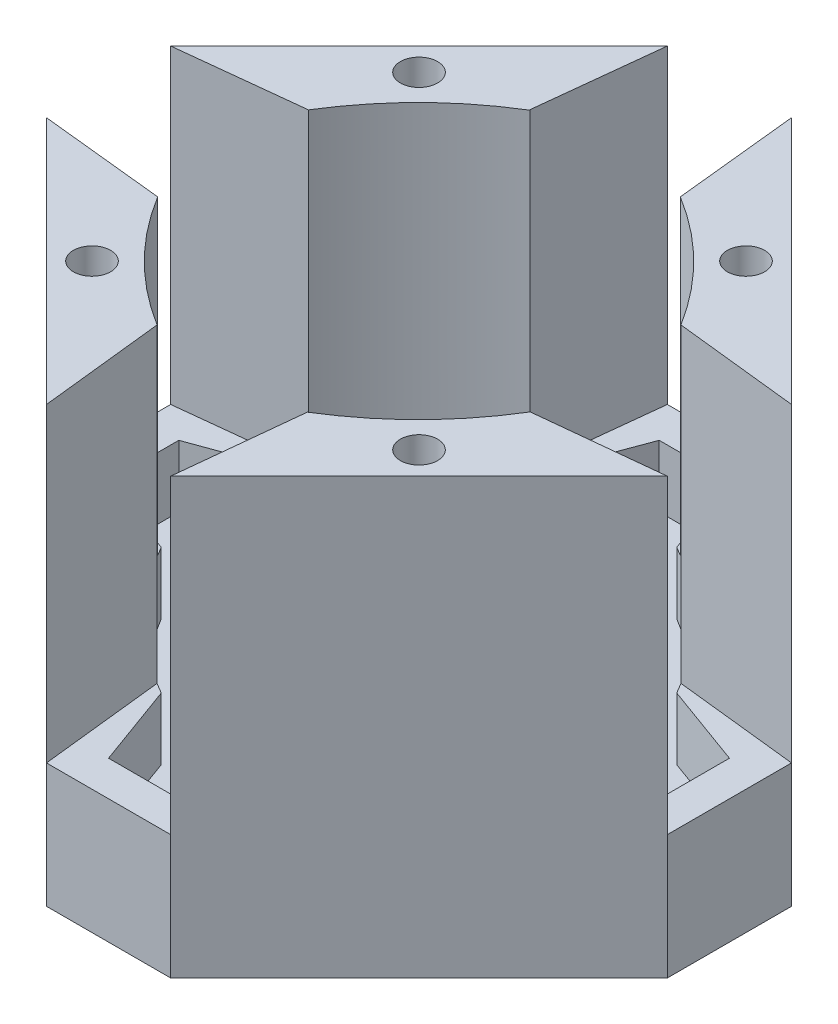
SolidWorks part; units mm, degrees
ref_plane "Front Plane" through (0, 0, 0) normal (0, 0, 1) x (1, 0, 0)
ref_plane "Top Plane" through (0, 0, 0) normal (0, 1, 0) x (1, 0, 0)
ref_plane "Right Plane" through (0, 0, 0) normal (1, 0, 0) x (0, 0, -1)
sketch "Sketch1" plane through (0, 0, 0) normal (0, 1, 0) x (1, 0, 0)
  line L1 (-25, -25) -> (25, -25)
  line L2 (-25, -25) -> (-25, 25)
  line L3 (-25, 25) -> (25, 25)
  line L4 (25, -25) -> (25, 25)
  line L5 (-25, -25) -> (25, 25) construction
  line L6 (-25, 25) -> (25, -25) construction
  circle A0 centre (0, 0) radius 4.5
  point P0 (0, 0)
  dimension "D3" = 9
  dimension "D1" = 50
  dimension "D2" = 50
extrude "Boss-Extrude1" add sketch "Sketch1" along normal blind 5
sketch "Sketch2" plane through (0, 5, 0) normal (0, 1, 0) x (1, 0, 0)
  line L0 (-25, 25) -> (25, -25) construction
  line L1 (25, 25) -> (-25, -25) construction
  line L2 (0, 0) -> (-0.0589, 16.2499) construction
  line L3 (-25, 25) -> (-25, -25) construction
  line L4 (0, -25) -> (0, 25) construction
  line L5 (-25, 25) -> (-25, 5)
  line L6 (-25, 25) -> (-5, 25)
  line L7 (25, 25) -> (-25, 25) construction
  line L8 (-25, 5) -> (-5, 25)
  line L9 (-25, -25) -> (25, -25) construction
  line L10 (25, -25) -> (5, -25)
  line L11 (25, -25) -> (25, -5)
  line L12 (5, -25) -> (25, -5)
  line L13 (-25, -25) -> (-25, -5)
  line L14 (-5, -25) -> (-25, -5)
  line L15 (-25, -25) -> (-5, -25)
  line L16 (25, 25) -> (25, 5)
  line L17 (25, 25) -> (5, 25)
  line L18 (25, 5) -> (5, 25)
  circle A1 centre (-0.0589, 16.2499) radius 2
  circle A2 centre (16.2499, -0.0589) radius 2
  circle A3 centre (0.0589, -16.2499) radius 2
  circle A4 centre (-16.2499, 0.0589) radius 2
  dimension "D1" = 20
  dimension "D3" = 20
  dimension "D2" = 16.25
extrude "Cut-Extrude1" cut sketch "Sketch2" against normal through all
sketch "Sketch3" plane through (0, 5, 0) normal (0, 1, 0) x (1, 0, 0)
  line L0 (15, 15) -> (12.5, 12.5) construction
  line L1 (5, 25) -> (25, 5) construction
  line L2 (-5, -25) -> (-25, -5) construction
  line L3 (0, -4.5) -> (-0.4286, -4.9286)
  line L4 (-22.1716, 2.8284) -> (-2.8284, 22.1716) construction
  line L5 (-7.8284, 22.1716) -> (-25, 5)
  line L7 (2.8284, 22.1716) -> (22.1716, 2.8284) construction
  line L9 (22.1716, -2.8284) -> (2.8284, -22.1716) construction
  line L10 (-5, -25) -> (5, -25) construction
  line L11 (-2.8284, -22.1716) -> (-22.1716, -2.8284) construction
  line L12 (-22.1716, -2.8284) -> (-2.8284, -22.1716)
  line L13 (-25, 5) -> (-22.1716, 7.8284) construction
  line L14 (-25, 5) -> (-5, 25) construction
  line L15 (-25, -5) -> (-22.1716, -7.8284) construction
  line L16 (-22.1716, -2.8284) -> (-22.1716, 2.8284)
  line L17 (-22.1716, 7.8284) -> (-25, 5)
  line L18 (-25, 5) -> (-25, -5)
  line L19 (-25, -5) -> (-22.1716, -7.8284)
  line L20 (-5, -25) -> (0, -25)
  line L21 (-22.1716, -7.8284) -> (-5, -25)
  line L22 (-2.8284, -22.1716) -> (2.8284, -22.1716)
  line L23 (5, -25) -> (-5, -25)
  line L24 (7.8284, -22.1716) -> (5, -25)
  line L27 (22.1716, -7.8284) -> (25, -5)
  line L28 (25, -5) -> (25, 5)
  line L29 (22.1716, 2.8284) -> (22.1716, -2.8284)
  line L30 (2.8284, 22.1716) -> (22.1716, 2.8284)
  line L31 (7.8284, 22.1716) -> (25, 5)
  line L32 (-5, 25) -> (5, 25)
  line L33 (-7.8284, 22.1716) -> (-5, 25)
  line L34 (2.8284, 22.1716) -> (-2.8284, 22.1716)
  line L35 (-22.1716, 7.8284) -> (-7.8284, 22.1716)
  line L36 (-22.1716, 2.8284) -> (-2.8284, 22.1716)
  line L37 (2.8284, -22.1716) -> (22.1716, -2.8284)
  line L38 (7.8284, -22.1716) -> (22.1716, -7.8284)
  line L39 (-22.1716, 7.8284) -> (-7.8284, 22.1716)
  circle A1 centre (0, 0) radius 4.5 construction
  line M24 (25, -5) -> (25, 5)
  line M25 (25, 5) -> (5, 25)
  line M26 (5, 25) -> (-5, 25)
  line M27 (-5, 25) -> (-25, 5)
  line M28 (-25, 5) -> (-25, -5)
  line M29 (-25, -5) -> (-5, -25)
  line M30 (-5, -25) -> (5, -25)
  line M31 (5, -25) -> (25, -5)
  dimension "D1" = 4
  dimension "D2" = 4
extrude "Boss-Extrude2" add sketch "Sketch3" along normal blind 30 contours L5 L37 L22 L12 L16 L36 L34 L30 L29 M31 M24 M25 M26 M27 M28 M29 M30
sketch "Sketch4" plane through (0, 35, 0) normal (0, 1, 0) x (1, 0, 0)
  line L1 (-22.1716, -2.8284) -> (-2.8284, -22.1716) construction
  line L4 (-7.3747, -17.6253) -> (-17.537, -7.463)
  line L5 (-15.4156, -5.3417) -> (-22.1716, -2.8284)
  line L6 (-22.1716, -2.8284) -> (-17.537, -7.463)
  line L9 (-17.537, -7.463) -> (-2.8284, -22.1716)
  line L10 (-2.8284, -22.1716) -> (-5.2533, -15.504)
  line L11 (-7.3747, -17.6253) -> (-2.8284, -22.1716)
  line L15 (2.8284, 22.1716) -> (7.463, 17.537)
  line L16 (5.3417, 15.4156) -> (2.8284, 22.1716)
  line L17 (22.1716, 2.8284) -> (15.504, 5.2533)
  line L18 (7.463, 17.537) -> (22.1716, 2.8284)
  line L22 (-5.3417, 15.4156) -> (-2.8284, 22.1716)
  line L23 (-22.1716, 2.8284) -> (-15.504, 5.2533)
  line L24 (-7.463, 17.537) -> (-22.1716, 2.8284)
  line L25 (-2.8284, 22.1716) -> (-7.463, 17.537)
  line L26 (22.1716, -2.8284) -> (17.537, -7.463)
  line L27 (15.4156, -5.3417) -> (22.1716, -2.8284)
  line L28 (2.8284, -22.1716) -> (5.2533, -15.504)
  line L29 (17.537, -7.463) -> (2.8284, -22.1716)
  spline S0 degree 3 poles (-15.4156, -5.3417) (-12.8732, -9.7779) (-9.4021, -13.1087) (-5.2533, -15.504) knots 0 0 0 0 1 1 1 1
  spline S1 degree 3 poles (5.3417, 15.4156) (9.7779, 12.8732) (13.1087, 9.4021) (15.504, 5.2533) knots 0 0 0 0 1 1 1 1
  spline S2 degree 3 poles (-5.3417, 15.4156) (-9.7779, 12.8732) (-13.1087, 9.4021) (-15.504, 5.2533) knots 0 0 0 0 1 1 1 1
  spline S3 degree 3 poles (15.4156, -5.3417) (12.8732, -9.7779) (9.4021, -13.1087) (5.2533, -15.504) knots 0 0 0 0 1 1 1 1
  line M17 (22.1716, -2.8284) -> (2.8284, -22.1716)
  line M19 (-2.8284, -22.1716) -> (-22.1716, -2.8284)
  line M21 (-22.1716, 2.8284) -> (-2.8284, 22.1716)
  line M23 (2.8284, 22.1716) -> (22.1716, 2.8284)
  dimension "D1" = 3
  dimension "D3" = 3
extrude "Boss-Extrude3" add sketch "Sketch4" against normal blind 30 contours S2 L22 L23 M21 | L16 S1 L17 M23 | L27 S3 L28 M17 | S0 L5 L10 M19
sketch "Sketch7" plane through (0, 35, 0) normal (0, 1, 0) x (1, 0, 0)
  line L2 (-25, 5) -> (-25, -5)
  line L6 (0, 25) -> (0, -25) construction
  line L7 (5, 25) -> (-5, 25) construction
  line L8 (-5, -25) -> (5, -25) construction
  line L9 (-15, 15) -> (15, -15) construction
  line L10 (-5, 25) -> (-25, 5) construction
  line L11 (5, -25) -> (25, -5) construction
  line L12 (-25, 5) -> (-15, 6.094)
  line L13 (-25, -5) -> (-15, -6.0437)
  line L14 (-15, -6.0437) -> (-15, 6.094)
  line L15 (25, -5) -> (15, -6.0437)
  line L16 (25, 5) -> (25, -5)
  line L17 (25, 5) -> (15, 6.094)
  line L18 (15, -6.0437) -> (15, 6.094)
  line L19 (-5, -25) -> (5, -25)
  line L20 (-5, -25) -> (-6.094, -15)
  line L21 (6.0437, -15) -> (-6.094, -15)
  line L22 (5, -25) -> (6.0437, -15)
  line L23 (5, 25) -> (6.0437, 15)
  line L24 (-5, 25) -> (5, 25)
  line L25 (-5, 25) -> (-6.094, 15)
  line L26 (6.0437, 15) -> (-6.094, 15)
  spline S0 degree 3 poles (-5.3417, 15.4156) (-9.7779, 12.8732) (-13.1087, 9.4021) (-15.504, 5.2533) knots 0 0 0 0 1 1 1 1 construction
  spline S1 degree 3 poles (-15.4156, -5.3417) (-12.8732, -9.7779) (-9.4021, -13.1087) (-5.2533, -15.504) knots 0 0 0 0 1 1 1 1 construction
extrude "Cut-Extrude5" cut sketch "Sketch7" against normal blind 25
sketch "Sketch9" plane through (0, 5, 0) normal (0, 1, 0) x (1, 0, 0)
  line L0 (-25, 0) -> (25, 0) construction
  line L1 (-25, 5) -> (-25, -5) construction
  line L2 (25, -5) -> (25, 5) construction
  line L3 (-15, 15) -> (15, -15) construction
  line L4 (-5, 25) -> (-25, 5) construction
  line L5 (5, -25) -> (25, -5) construction
  circle A0 centre (0, 9.4999) radius 2.5
  circle A1 centre (-0.0589, 16.2499) radius 2 construction
  circle A2 centre (0, -9.4999) radius 2.5
  circle A3 centre (9.4999, 0) radius 2.5
  circle A4 centre (-9.4999, 0) radius 2.5
  dimension "D1" = 6.75
  dimension "D2" = 5
extrude "Cut-Extrude8" cut sketch "Sketch9" against normal through all
sketch "Sketch10" plane through (0, 35, 0) normal (0, 1, 0) x (1, 0, 0)
  line L0 (15, 15) -> (-15, -15) construction
  line L1 (25, 5) -> (5, 25) construction
  line L2 (-25, -5) -> (-5, -25) construction
  line L3 (25, 0) -> (-25, 0) construction
  line L4 (25, -5) -> (25, 5) construction
  line L5 (-25, 5) -> (-25, -5) construction
  line L6 (0, 25) -> (0, -25) construction
  line L7 (5, 25) -> (-5, 25) construction
  line L8 (-5, -25) -> (5, -25) construction
  circle A0 centre (13.1668, 13.1668) radius 1.5
  circle A1 centre (-13.1668, 13.1668) radius 1.5
  circle A2 centre (-13.1668, -13.1668) radius 1.5
  circle A3 centre (13.1668, -13.1668) radius 1.5
  dimension "D1" = 3
extrude "Cut-Extrude9" cut sketch "Sketch10" against normal blind 10
